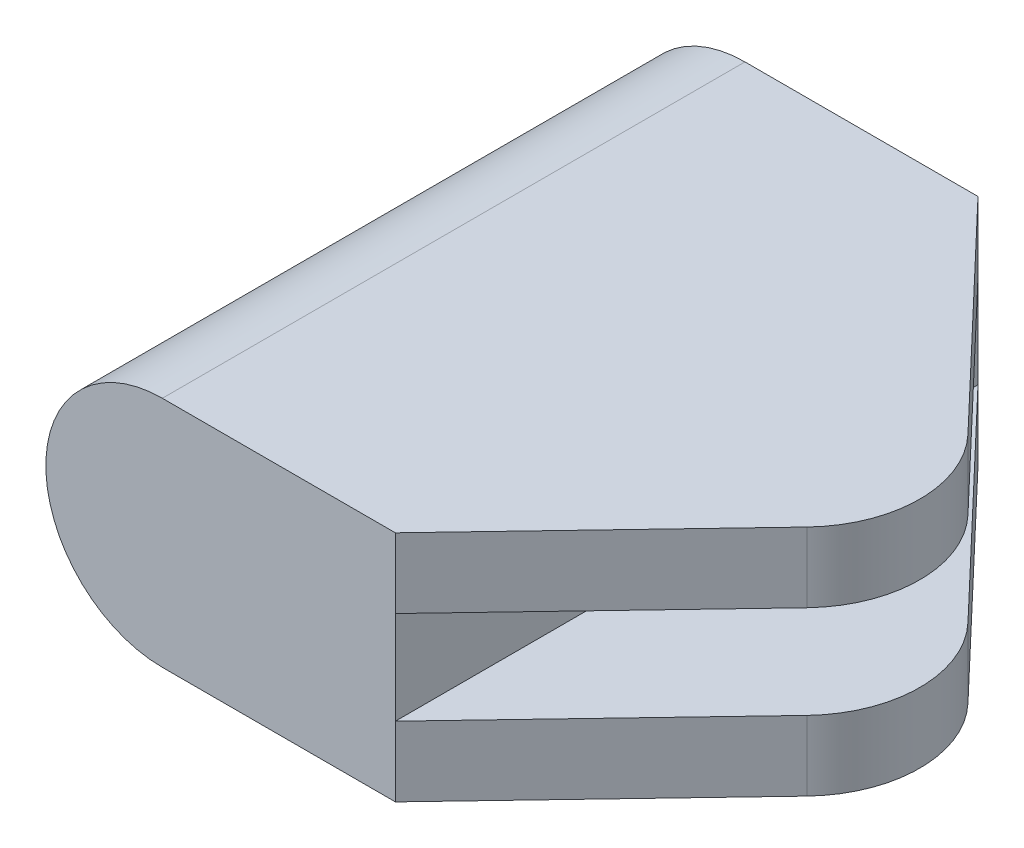
SolidWorks part; units mm, degrees
ref_plane "前视基准面" through (0, 0, 0) normal (0, 0, 1) x (1, 0, 0)
ref_plane "上视基准面" through (0, 0, 0) normal (0, 1, 0) x (1, 0, 0)
ref_plane "右视基准面" through (0, 0, 0) normal (1, 0, 0) x (0, 0, -1)
sketch "草图2" plane through (0, 0, 0) normal (0, 0, 1) x (1, 0, 0)
  line L0 (0, 20) -> (80, 20)
  line L1 (80, 20) -> (80, -20)
  line L2 (80, -20) -> (0, -20)
  arc A0 (0, 20) -> (0, -20) centre (0, 0) ccw
  dimension "D1" = 80
extrude "凸台-拉伸1" add sketch "草图2" along normal blind 100
sketch "草图3" plane through (0, 20, 0) normal (0, 1, 0) x (1, 0, 0)
  line L0 (80, -50) -> (-33.911, -50) construction
  line L1 (80, -100) -> (80, 0) construction
  line L2 (40, 0) -> (74.4828, -36.2069)
  line L3 (80, 0) -> (0, 0) construction
  line L4 (40, -100) -> (74.4828, -63.7931)
  line L5 (80, -100) -> (0, -100) construction
  line L6 (40, -100) -> (91.7144, -100)
  line L7 (91.7144, -100) -> (91.7144, 0)
  line L8 (91.7144, 0) -> (40, 0)
  arc A0 (74.4828, -63.7931) -> (74.4828, -36.2069) centre (60, -50) ccw
extrude "切除-拉伸1" cut sketch "草图3" against normal blind 100
sketch "草图5" plane through (0, 0, 0) normal (0, 1, 0) x (1, 0, 0)
  line L1 (40, 0) -> (83.9751, 0)
  line L2 (40, 0) -> (40, -100.1047)
  line L3 (40, -100.1047) -> (83.9751, -100.1047)
  line L4 (83.9751, 0) -> (83.9751, -100.1047)
extrude "切除-拉伸3" cut sketch "草图5" against normal mid plane 16
